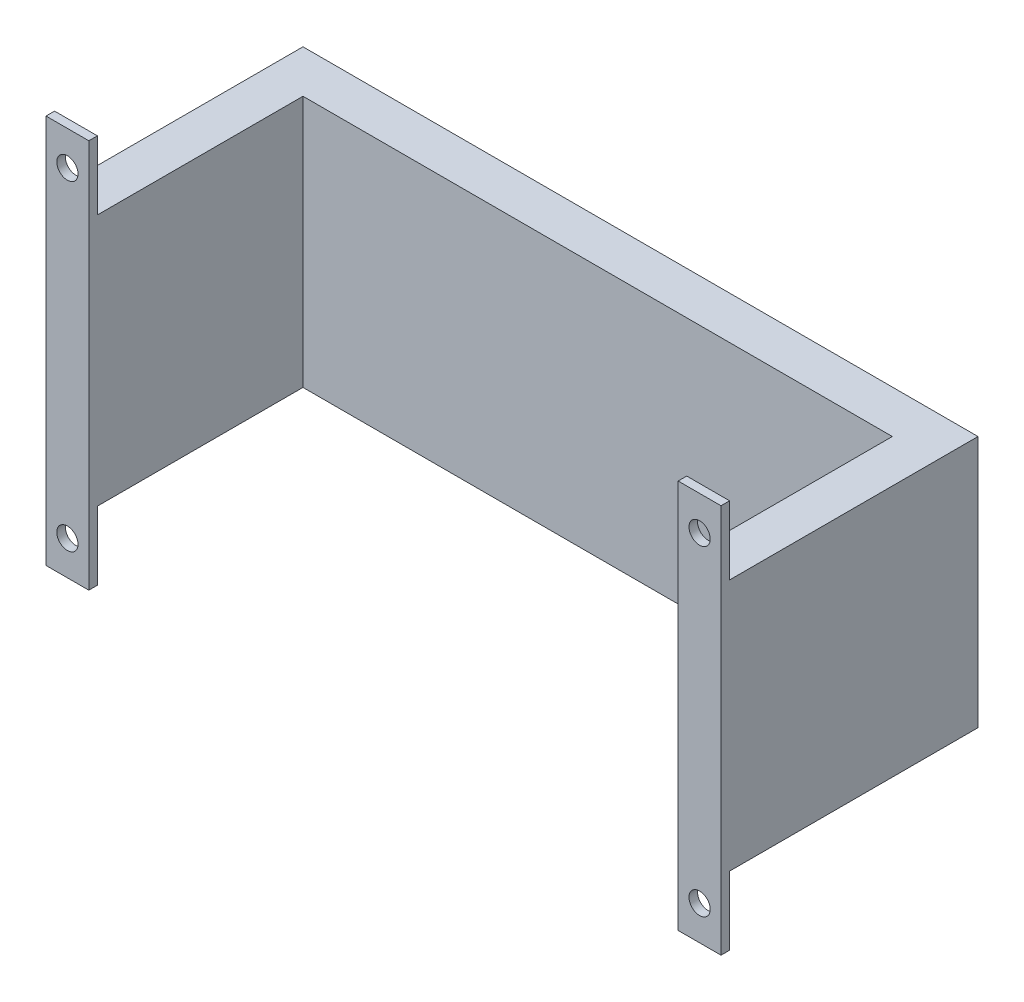
SolidWorks part; units mm, degrees
material "1060 Alloy"
ref_plane "Front Plane" through (0, 0, 0) normal (0, 0, 1) x (1, 0, 0)
ref_plane "Top Plane" through (0, 0, 0) normal (0, 1, 0) x (1, 0, 0)
ref_plane "Right Plane" through (0, 0, 0) normal (1, 0, 0) x (0, 0, -1)
sketch "Sketch1" plane through (0, 0, 0) normal (0, 0, 1) x (1, 0, 0)
  line L1 (125.095, -46.736) -> (-125.095, -46.736)
  line L2 (125.095, -46.736) -> (125.095, 46.736)
  line L3 (125.095, 46.736) -> (-125.095, 46.736)
  line L4 (-125.095, -46.736) -> (-125.095, 46.736)
  line L5 (125.095, -46.736) -> (-125.095, 46.736) construction
  line L6 (125.095, 46.736) -> (-125.095, -46.736) construction
  point P0 (0, 0)
  dimension "D1" = 93.472
  dimension "D2" = 250.19
extrude "Boss-Extrude1" add sketch "Sketch1" along normal blind 95.25
sketch "Sketch5" plane through (0, 0, 95.25) normal (0, 0, 1) x (1, 0, 0)
  line L1 (109.22, -46.736) -> (-109.22, -46.736)
  line L2 (109.22, -46.736) -> (109.22, 46.736)
  line L3 (109.22, 46.736) -> (-109.22, 46.736)
  line L4 (-109.22, -46.736) -> (-109.22, 46.736)
  line L5 (109.22, -46.736) -> (-109.22, 46.736) construction
  line L6 (109.22, 46.736) -> (-109.22, -46.736) construction
  point P0 (0, 0)
  dimension "D1" = 93.472
  dimension "D2" = 218.44
extrude "Cut-Extrude1" cut sketch "Sketch5" against normal blind 79.375
sketch "Sketch6" plane through (0, 0, 95.25) normal (0, 0, 1) x (1, 0, 0)
  line L1 (109.22, 72.136) -> (125.095, 72.136)
  line L2 (109.22, 72.136) -> (109.22, 46.736)
  line L3 (109.22, 46.736) -> (125.095, 46.736)
  line L4 (125.095, 72.136) -> (125.095, 46.736)
  line L5 (109.22, 72.136) -> (125.095, 46.736) construction
  line L6 (109.22, 46.736) -> (125.095, 72.136) construction
  line L8 (125.095, 46.736) -> (109.22, 46.736) construction
  line L9 (125.095, -46.736) -> (125.095, 46.736) construction
  line L11 (0, -51.4096) -> (0, 51.4096) construction
  line L12 (-109.22, 46.736) -> (-125.095, 46.736)
  line L13 (-125.095, 72.136) -> (-125.095, 46.736)
  line L14 (-109.22, 72.136) -> (-125.095, 72.136)
  line L15 (-109.22, 72.136) -> (-109.22, 46.736)
  line L16 (52.3875, 0) -> (-52.3875, 0) construction
  line L17 (109.22, -46.736) -> (125.095, -46.736)
  line L18 (125.095, -72.136) -> (125.095, -46.736)
  line L19 (109.22, -72.136) -> (125.095, -72.136)
  line L20 (109.22, -72.136) -> (109.22, -46.736)
  line L21 (-109.22, -72.136) -> (-109.22, -46.736)
  line L22 (-109.22, -72.136) -> (-125.095, -72.136)
  line L23 (-125.095, -72.136) -> (-125.095, -46.736)
  line L24 (-109.22, -46.736) -> (-125.095, -46.736)
  point P0 (117.1575, 59.436)
  dimension "D1" = 15.875
  dimension "D4" = 25.4
extrude "Boss-Extrude2" add sketch "Sketch6" against normal blind 3.175
sketch "Sketch7" plane through (0, 0, 92.075) normal (0, 0, -1) x (-1, 0, 0)
  line L0 (117.1575, 72.136) -> (117.1575, 46.736) construction
  line L1 (109.22, 72.136) -> (125.095, 72.136) construction
  line L2 (125.095, 46.736) -> (109.22, 46.736) construction
  line L3 (109.22, 59.436) -> (125.095, 59.436) construction
  line L4 (109.22, 46.736) -> (109.22, 72.136) construction
  line L5 (125.095, 72.136) -> (125.095, 46.736) construction
  line L6 (0, 51.4096) -> (0, -51.4096) construction
  line L7 (52.3875, 0) -> (-52.3875, 0) construction
  circle A0 centre (117.1575, 59.436) radius 3.937
  circle A1 centre (-117.1575, 59.436) radius 3.937
  circle A2 centre (117.1575, -59.436) radius 3.937
  circle A3 centre (-117.1575, -59.436) radius 3.937
  dimension "D1" = 7.874
extrude "Cut-Extrude2" cut sketch "Sketch7" against normal through all
equation "\"Height\"=3.68"
equation "\"D1@Sketch1\"=\"Height\""
equation "\"D1@Sketch5\"=\"Height\""
